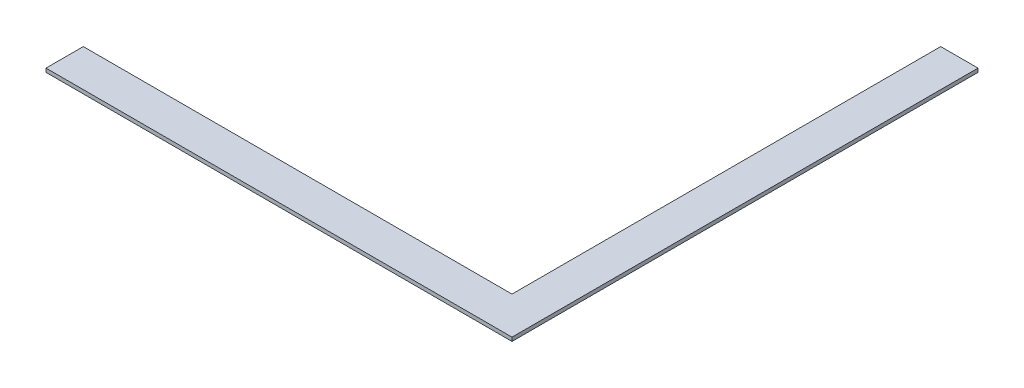
SolidWorks part; units mm, degrees
ref_plane "Front Plane" through (0, 0, 0) normal (0, 0, 1) x (1, 0, 0)
ref_plane "Top Plane" through (0, 0, 0) normal (0, 1, 0) x (1, 0, 0)
ref_plane "Right Plane" through (0, 0, 0) normal (1, 0, 0) x (0, 0, -1)
sketch "Sketch1" plane through (0, 0, 0) normal (0, 1, 0) x (1, 0, 0)
  line L0 (0, 0) -> (250, 0)
  line L1 (250, 0) -> (250, 250)
  line L2 (250, 250) -> (230, 250)
  line L3 (230, 250) -> (230, 20)
  line L4 (230, 20) -> (0, 20)
  line L5 (0, 20) -> (0, 0)
  dimension "D1" = 20
  dimension "D2" = 20
  dimension "D3" = 250
  dimension "D4" = 250
extrude "Boss-Extrude1" add sketch "Sketch1" along normal blind 2
